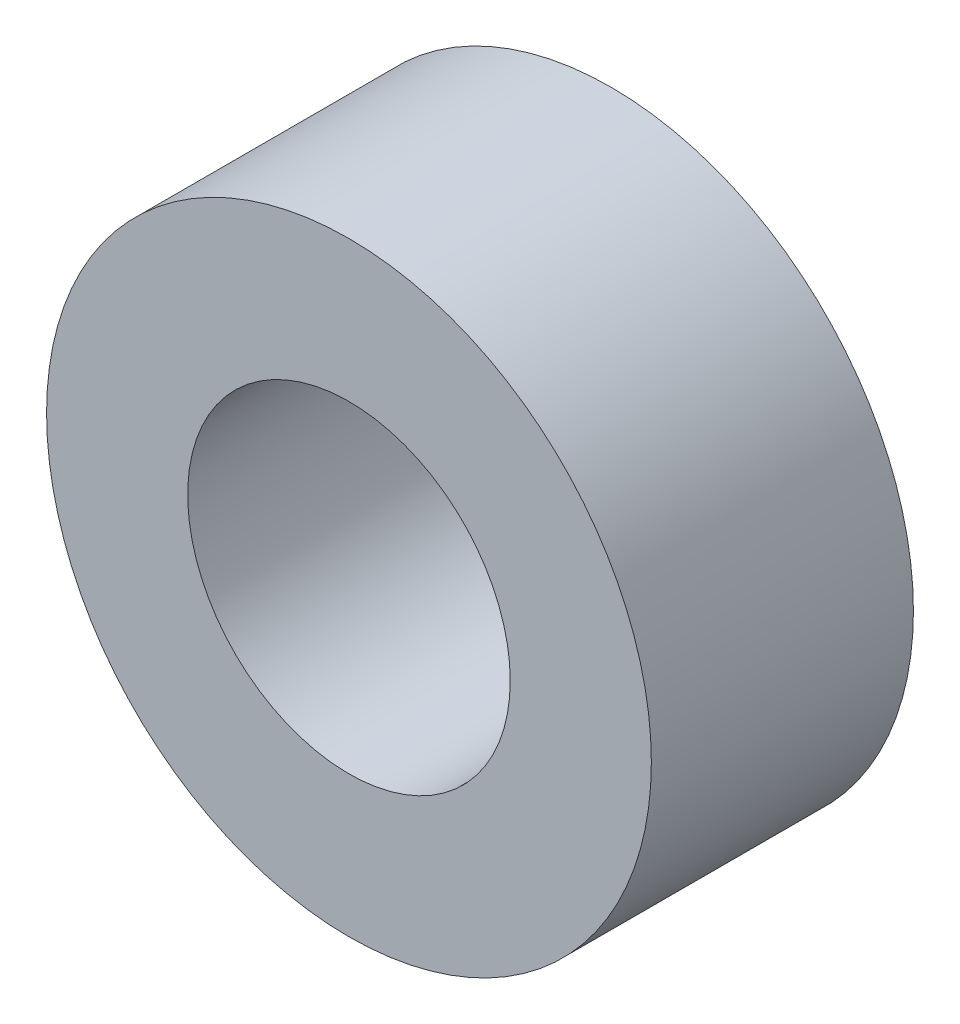
SolidWorks part; units mm, degrees
ref_plane "Plan de face" through (0, 0, 0) normal (0, 0, 1) x (1, 0, 0)
ref_plane "Plan de dessus" through (0, 0, 0) normal (0, 1, 0) x (1, 0, 0)
ref_plane "Plan de droite" through (0, 0, 0) normal (1, 0, 0) x (0, 0, -1)
sketch "Esquisse1" plane through (0, 0, 0) normal (0, 0, 1) x (1, 0, 0)
  circle A0 centre (0, 0) radius 7.5
  dimension "D1" = 15
extrude "Boss.-Extru.1" add sketch "Esquisse1" along normal blind 6.5
sketch "Esquisse2" plane through (0, 0, 6.5) normal (0, 0, 1) x (1, 0, 0)
  circle A0 centre (0, 0) radius 4
  dimension "D1" = 8
extrude "Enlèv. mat.-Extru.1" cut sketch "Esquisse2" against normal blind 6.5
